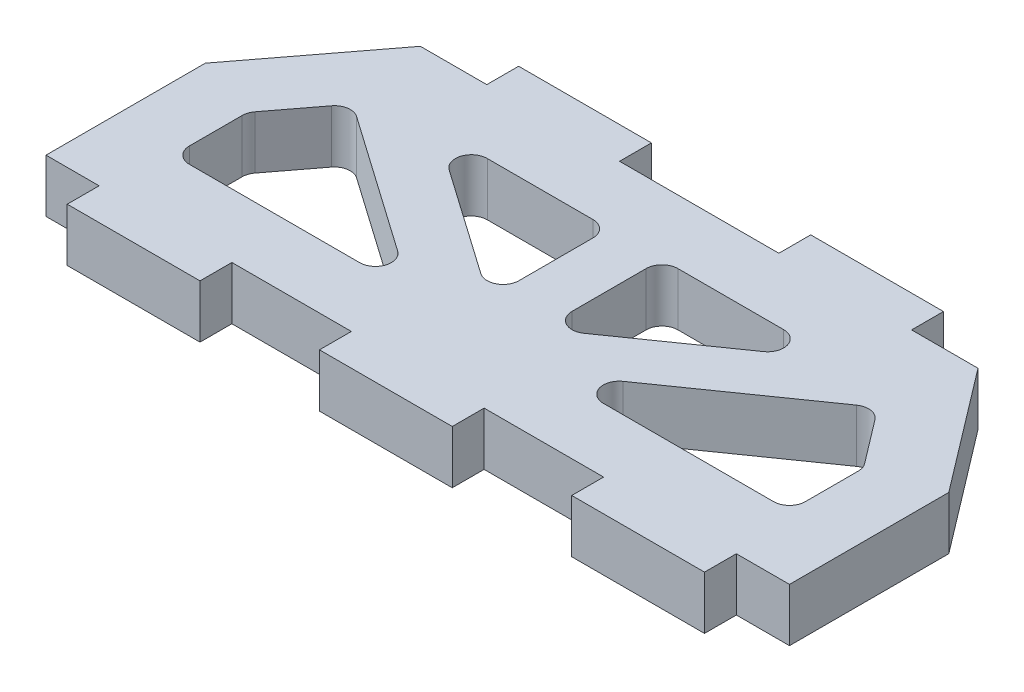
SolidWorks part; units mm, degrees
ref_plane "前视基准面" through (0, 0, 0) normal (0, 0, 1) x (1, 0, 0)
ref_plane "上视基准面" through (0, 0, 0) normal (0, 1, 0) x (1, 0, 0)
ref_plane "右视基准面" through (0, 0, 0) normal (1, 0, 0) x (0, 0, -1)
sketch "草图1" plane through (0, 0, 0) normal (0, 1, 0) x (1, 0, 0)
  line L0 (-347.0136, 0) -> (17003.6688, 0) construction
  line L1 (0, -347.0136) -> (0, 17003.6688) construction
  line L2 (6.25, -9.2191) -> (-6.25, -9.2191)
  line L3 (-6.25, -9.2191) -> (-6.25, -6.2191)
  line L4 (-6.25, -6.2191) -> (-17.5, -6.2191)
  line L5 (-17.5, -6.2191) -> (-17.5, -9.2191)
  line L6 (-17.5, -9.2191) -> (-30, -9.2191)
  line L7 (-30, -9.2191) -> (-30, -6.2191)
  line L8 (-30, -6.2191) -> (-35, -6.2191)
  line L9 (-35, -6.2191) -> (-35, 8.7809)
  line L10 (-35, 8.7809) -> (-26.25, 20.2809)
  line L11 (-26.25, 20.2809) -> (-20, 20.2809)
  line L12 (-20, 20.2809) -> (-20, 23.2809)
  line L13 (-20, 23.2809) -> (-7.5, 23.2809)
  line L14 (-7.5, 23.2809) -> (-7.5, 20.2809)
  line L15 (-7.5, 20.2809) -> (7.5, 20.2809)
  line L16 (7.5, 23.2809) -> (7.5, 20.2809)
  line L17 (20, 23.2809) -> (7.5, 23.2809)
  line L18 (20, 20.2809) -> (20, 23.2809)
  line L19 (26.25, 20.2809) -> (20, 20.2809)
  line L20 (35, 8.7809) -> (26.25, 20.2809)
  line L21 (35, -6.2191) -> (35, 8.7809)
  line L22 (30, -6.2191) -> (35, -6.2191)
  line L23 (30, -9.2191) -> (30, -6.2191)
  line L24 (17.5, -9.2191) -> (30, -9.2191)
  line L25 (17.5, -6.2191) -> (17.5, -9.2191)
  line L26 (6.25, -6.2191) -> (17.5, -6.2191)
  line L27 (6.25, -9.2191) -> (6.25, -6.2191)
  line L32 (-29, 6.7578) -> (-24.7187, 12.3847)
  line L33 (-29, 6.7578) -> (-29, -0.2191)
  line L34 (-29, -0.2191) -> (-6.7186, -0.2191)
  line L35 (-6.7186, -0.2191) -> (-24.7187, 12.3847)
  line L36 (-18.7095, 14.2809) -> (-2.5, 2.9309)
  line L37 (-2.5, 2.9309) -> (-2.5, 14.2809)
  line L38 (-2.5, 14.2809) -> (-18.7095, 14.2809)
  line L39 (2.5, 14.2809) -> (18.7095, 14.2809)
  line L40 (2.5, 2.9309) -> (2.5, 14.2809)
  line L41 (18.7095, 14.2809) -> (2.5, 2.9309)
  line L42 (6.7186, -0.2191) -> (24.7187, 12.3847)
  line L43 (29, -0.2191) -> (6.7186, -0.2191)
  line L44 (29, 6.7578) -> (29, -0.2191)
  line L45 (29, 6.7578) -> (24.7187, 12.3847)
  point P7 (-6.25, -7.7191)
  point P23 (0, 20.2809)
  point P35 (0, -9.2191)
  dimension "D1" = 12.5
  dimension "D2" = 3
  dimension "D3" = 70
  dimension "D4" = 11.25
  dimension "D5" = 15
  dimension "D6" = 26.5
  dimension "D7" = 15
  dimension "D8" = 12.5
  dimension "D9" = 52.5
  dimension "D10" = 3
  dimension "D11" = 12.5
  dimension "D12" = 6
  dimension "D13" = 6
  dimension "D14" = 6
  dimension "D15" = 35
  dimension "D16" = 5
  dimension "D17" = 6
  dimension "D18" = 11.35
  dimension "D19" = 5
extrude "凸台-拉伸1" add sketch "草图1" along normal blind 5
fillet "圆角1" radius 1.5 14 edges at (29, 2.5, 0.2191) (29, 2.5, -6.7578) (24.7187, 2.5, -12.3847) (6.7186, 2.5, 0.2191) (2.5, 2.5, -2.9309) (18.7095, 2.5, -14.2809) (2.5, 2.5, -14.2809) (-2.5, 2.5, -2.9309) (-2.5, 2.5, -14.2809) (-18.7095, 2.5, -14.2809) (-6.7186, 2.5, 0.2191) (-29, 2.5, 0.2191) (-24.7187, 2.5, -12.3847) (-29, 2.5, -6.7578)
